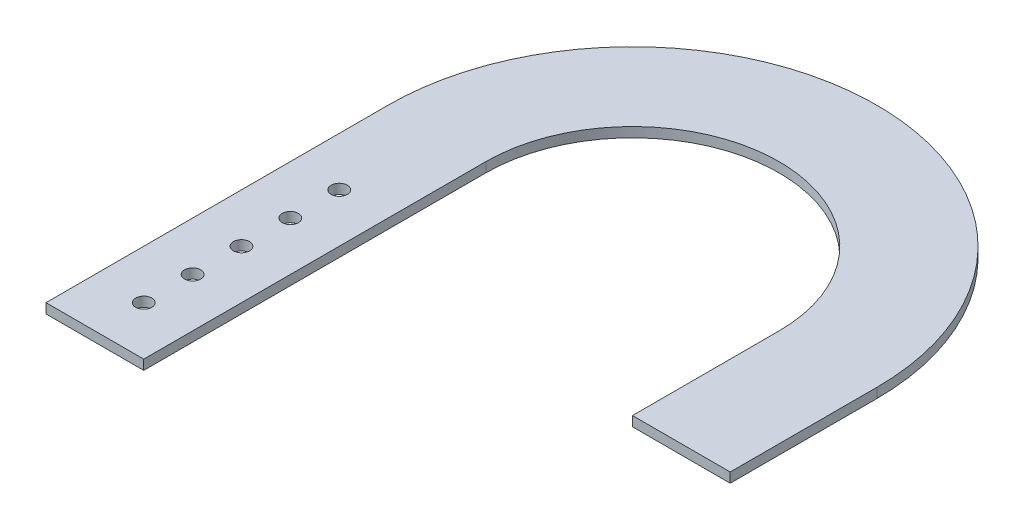
SolidWorks part; units mm, degrees
ref_plane "Front Plane" through (0, 0, 0) normal (0, 0, 1) x (1, 0, 0)
ref_plane "Top Plane" through (0, 0, 0) normal (0, 1, 0) x (1, 0, 0)
ref_plane "Right Plane" through (0, 0, 0) normal (1, 0, 0) x (0, 0, -1)
sketch "Sketch1" plane through (0, 0, 0) normal (0, 1, 0) x (1, 0, 0)
  line L28 (-38.1, -88.9) -> (-38.1, 0)
  line L29 (38.1, 0) -> (38.1, -38.1)
  line L30 (38.1, -38.1) -> (63.5, -38.1)
  line L31 (63.5, -38.1) -> (63.5, 0)
  line L32 (-63.5, 0) -> (-63.5, -88.9)
  line L33 (-63.5, -88.9) -> (-38.1, -88.9)
  line L34 (-38.1, -88.9) -> (-38.1, 0)
  line L35 (38.1, 0) -> (38.1, -38.1)
  line L36 (38.1, -38.1) -> (63.5, -38.1)
  line L37 (63.5, -38.1) -> (63.5, 0)
  line L38 (-63.5, 0) -> (-63.5, -88.9)
  line L39 (-63.5, -88.9) -> (-38.1, -88.9)
  arc A9 (38.1, 0) -> (-38.1, 0) centre (0, 0) ccw
  arc A10 (63.5, 0) -> (-63.5, 0) centre (0, 0) ccw
  arc A11 (38.1, 0) -> (-38.1, 0) centre (0, 0) ccw
  arc A12 (63.5, 0) -> (-63.5, 0) centre (0, 0) ccw
  dimension "D1" = 0
extrude "Boss-Extrude1" add sketch "Sketch1" along normal blind 2.54
sketch "Sketch2" plane through (0, 2.54, 0) normal (0, 1, 0) x (1, 0, 0)
  line L1 (-63.5, -88.9) -> (-38.1, -88.9) construction
  circle A0 centre (-50.8, -76.2) radius 2.0955
  circle A1 centre (-50.8, -63.5) radius 2.0955
  circle A2 centre (-50.8, -50.8) radius 2.0955
  circle A3 centre (-50.8, -38.1) radius 2.0955
  circle A4 centre (-50.8, -25.4) radius 2.0955
  point P5 (-50.8, -88.9)
  dimension "D1" = 4.191
  dimension "D2" = 12.7
  dimension "D5" = 12.7
  dimension "D4" = 5
extrude "Cut-Extrude1" cut sketch "Sketch2" against normal through all
